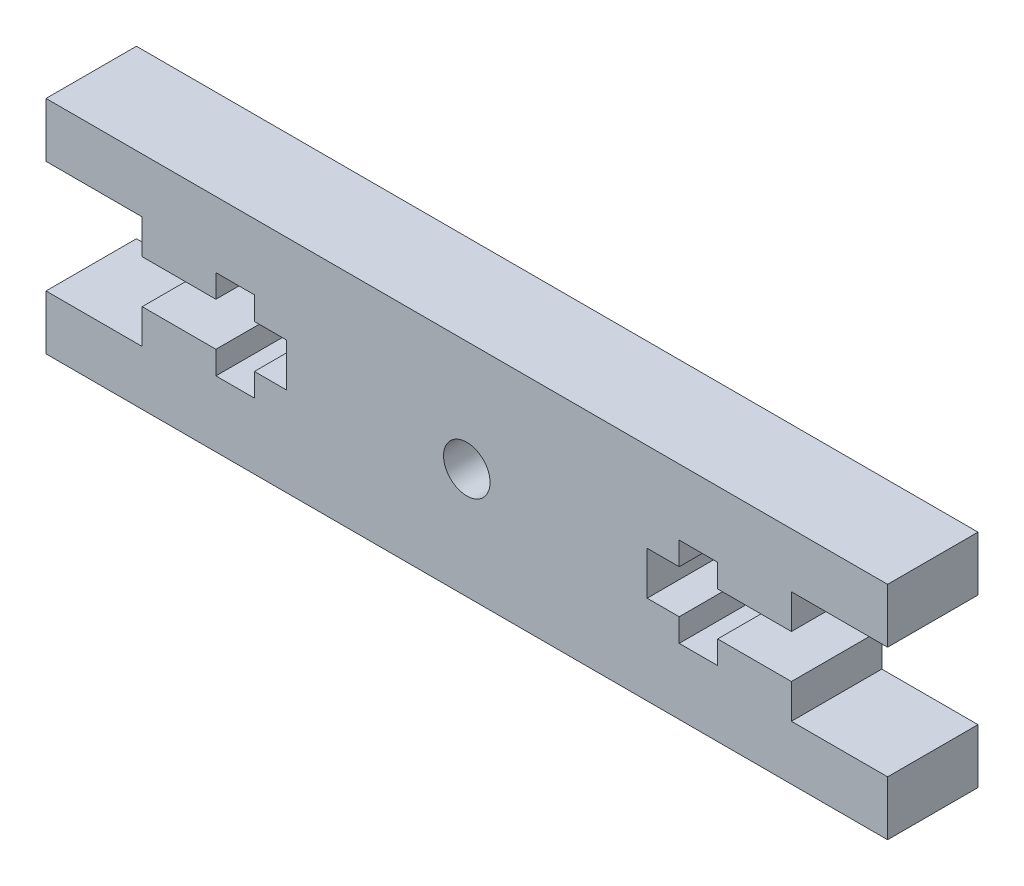
SolidWorks part; units mm, degrees
material "Acrylic (Medium-high impact)"
ref_plane "Front Plane" through (0, 0, 0) normal (0, 0, 1) x (1, 0, 0)
ref_plane "Top Plane" through (0, 0, 0) normal (0, 1, 0) x (1, 0, 0)
ref_plane "Right Plane" through (0, 0, 0) normal (1, 0, 0) x (0, 0, -1)
sketch "Sketch1" plane through (0, 0, 0) normal (0, 0, 1) x (1, 0, 0)
  line L0 (727.3394, 349.1985) -> (779.8394, 349.1985)
  line L1 (753.5894, -654.3154) -> (753.5894, 49345.6846) construction
  line L2 (742.3394, 343.6485) -> (742.3394, 340.9485)
  line L3 (727.3394, 345.7985) -> (733.3394, 345.7985)
  line L4 (733.3394, 345.7985) -> (733.3394, 343.6485)
  line L5 (733.3394, 343.6485) -> (737.9394, 343.6485)
  line L6 (737.9394, 345.0885) -> (740.3394, 345.0885)
  line L7 (-245.8122, 342.2985) -> (49754.1878, 342.2985) construction
  line L8 (727.3394, 335.3985) -> (727.3394, 338.7985)
  line L9 (737.9394, 340.9485) -> (737.9394, 339.5085)
  line L10 (740.3394, 339.5085) -> (740.3394, 340.9485)
  line L11 (740.3394, 340.9485) -> (742.3394, 340.9485)
  line L12 (737.9394, 339.5085) -> (740.3394, 339.5085)
  line L13 (733.3394, 340.9485) -> (737.9394, 340.9485)
  line L14 (740.3394, 343.6485) -> (742.3394, 343.6485)
  line L15 (740.3394, 345.0885) -> (740.3394, 343.6485)
  line L16 (733.3394, 338.7985) -> (733.3394, 340.9485)
  line L17 (737.9394, 343.6485) -> (737.9394, 345.0885)
  line L18 (727.3394, 338.7985) -> (733.3394, 338.7985)
  line L19 (727.3394, 335.3985) -> (779.8394, 335.3985)
  line L20 (779.8394, 349.1985) -> (779.8394, 345.7985)
  line L21 (779.8394, 338.7985) -> (773.8394, 338.7985)
  line L22 (769.2394, 343.6485) -> (769.2394, 345.0885)
  line L23 (773.8394, 338.7985) -> (773.8394, 340.9485)
  line L24 (766.8394, 345.0885) -> (766.8394, 343.6485)
  line L25 (766.8394, 343.6485) -> (764.8394, 343.6485)
  line L26 (773.8394, 340.9485) -> (769.2394, 340.9485)
  line L27 (769.2394, 339.5085) -> (766.8394, 339.5085)
  line L28 (766.8394, 340.9485) -> (764.8394, 340.9485)
  line L29 (766.8394, 339.5085) -> (766.8394, 340.9485)
  line L30 (769.2394, 340.9485) -> (769.2394, 339.5085)
  line L31 (779.8394, 335.3985) -> (779.8394, 338.7985)
  line L32 (769.2394, 345.0885) -> (766.8394, 345.0885)
  line L33 (773.8394, 343.6485) -> (769.2394, 343.6485)
  line L34 (727.3394, 349.1985) -> (727.3394, 345.7985)
  line L35 (773.8394, 345.7985) -> (773.8394, 343.6485)
  line L36 (779.8394, 345.7985) -> (773.8394, 345.7985)
  line L37 (764.8394, 343.6485) -> (764.8394, 340.9485)
  circle A0 centre (753.5894, 342.2985) radius 1.45
  point P7 (753.5894, 349.1985)
  point P8 (764.8394, 342.2985)
  point P24 (742.3394, 342.2985)
  point P28 (753.5894, 335.3985)
  point P46 (753.5894, 349.1985)
  dimension "D1" = 3.4
  dimension "D10" = 2.9
  dimension "D2" = 7
  dimension "D3" = 6
  dimension "D4" = 1.44
  dimension "D5" = 2.4
  dimension "D6" = 7
  dimension "D9" = 2.7
extrude "Boss-Extrude2" add sketch "Sketch1" along normal blind 5.64
